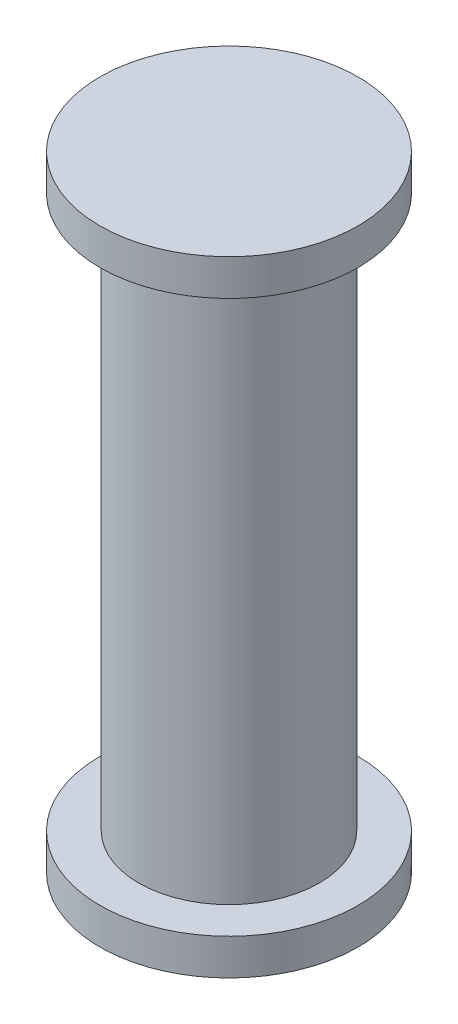
SolidWorks part; units mm, degrees
ref_plane "Płaszczyzna przednia" through (0, 0, 0) normal (0, 0, 1) x (1, 0, 0)
ref_plane "Płaszczyzna górna" through (0, 0, 0) normal (0, 1, 0) x (1, 0, 0)
ref_plane "Płaszczyzna prawa" through (0, 0, 0) normal (1, 0, 0) x (0, 0, -1)
sketch "Szkic1" plane through (0, 0, 0) normal (0, 1, 0) x (1, 0, 0)
  circle A0 centre (0, 0) radius 1.75
  dimension "D1" = 3.5
extrude "Dodanie-wyciągnięcie1" add sketch "Szkic1" along normal blind 10.7
sketch "Szkic2" plane through (0, 10.7, 0) normal (0, 1, 0) x (1, 0, 0)
  circle A0 centre (0, 0) radius 2.5
  dimension "D1" = 5
extrude "Dodanie-wyciągnięcie2" add sketch "Szkic2" along normal blind 0.7
sketch "Szkic3" plane through (0, 0, 0) normal (0, -1, 0) x (1, 0, 0)
  circle A0 centre (0, 0) radius 2.5
  dimension "D1" = 5
extrude "Dodanie-wyciągnięcie3" add sketch "Szkic3" along normal blind 0.7
